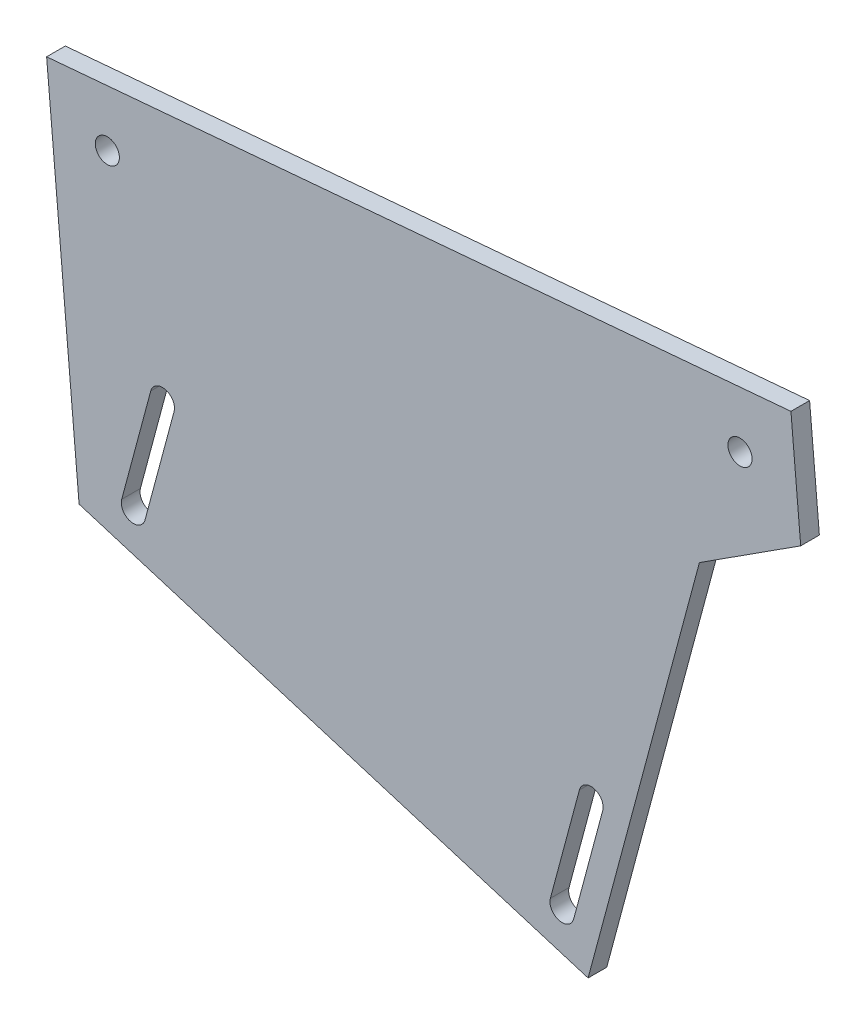
SolidWorks part; units mm, degrees
material "7075-T6, Plate (SS)"
ref_plane "Front Plane" through (0, 0, 0) normal (0, 0, 1) x (1, 0, 0)
ref_plane "Top Plane" through (0, 0, 0) normal (0, 1, 0) x (1, 0, 0)
ref_plane "Right Plane" through (0, 0, 0) normal (1, 0, 0) x (0, 0, -1)
sketch "Sketch1" plane through (0, 0, 0) normal (0, 0, 1) x (1, 0, 0)
  line L0 (-147.2071, -39.444) -> (0, 0) construction
  line L1 (0, 0) -> (-152.4, 0) construction
  line L2 (-425.45, 19.05) -> (-152.3665, -57.782)
  line L3 (-425.45, 57.15) -> (19.05, 57.15)
  line L4 (-425.45, 57.15) -> (-425.45, 19.05)
  line L6 (19.05, 57.15) -> (19.05, 0)
  line L7 (4.9305, -18.4009) -> (-142.2766, -57.8449)
  line L9 (-410.6516, 28.575) -> (19.05, 28.575) construction
  line L10 (-410.6516, 28.575) -> (-410.6516, -47.625) construction
  line L11 (-410.6516, -47.625) -> (19.05, -47.625) construction
  line L12 (19.05, 28.575) -> (19.05, -47.625) construction
  circle A0 centre (0, 0) radius 4.1021
  arc A1 (-152.4, 0) -> (-147.2071, -39.444) centre (0, 0) ccw construction
  arc A2 (-156.5021, 0) -> (-151.1694, -40.5057) centre (0, 0) ccw
  arc A3 (-148.2979, 0) -> (-143.2448, -38.3823) centre (0, 0) ccw
  arc A4 (-156.5021, 0) -> (-148.2979, 0) centre (-152.4, 0) cw
  arc A5 (-151.1694, -40.5057) -> (-143.2448, -38.3823) centre (-147.2071, -39.444) ccw
  circle A6 centre (-406.4, 38.1) radius 4.1021
  circle A7 centre (-101.6, 38.1) radius 4.1021
  arc A8 (-152.3665, -57.782) -> (-142.2766, -57.8449) centre (-147.2071, -39.444) ccw
  arc A9 (4.9305, -18.4009) -> (19.05, 0) centre (0, 0) ccw
  point P20 (19.05, -14.6176)
  dimension "D1" = 8.2042
  dimension "D2" = 152.4
  dimension "D6" = 304.8
  dimension "D3" = 15
  dimension "D7" = 38.1
  dimension "D8" = 101.6
  dimension "D9" = 19.05
  dimension "D10" = 19.05
  dimension "D11" = 19.05
  dimension "D13" = 19.05
  dimension "D16" = 76.2
  dimension "D4" = 4.1021
  dimension "D5" = 4.1021
extrude "Boss-Extrude1" [suppressed] add sketch "Sketch1" along normal blind 6.35
sketch "Sketch2" plane through (0, 0, 0) normal (0, 0, 1) x (1, 0, 0)
  line L0 (184.4812, 121.5931) -> (399.5596, 140.4101) construction
  line L1 (0, 0) -> (530.3185, 0) construction
  line L2 (0, 0) -> (0, 76.2) construction
  line L3 (0, 76.2) -> (530.3185, 76.2) construction
  line L4 (530.3185, 0) -> (530.3185, 76.2) construction
  line L5 (0, 0) -> (530.3185, 0) construction
  line L6 (0, 0) -> (0, 19.05) construction
  line L7 (0, 19.05) -> (530.3185, 19.05) construction
  line L8 (530.3185, 0) -> (530.3185, 19.05) construction
  line L9 (0, 76.2) -> (530.3185, 76.2) construction
  line L10 (0, 76.2) -> (0, 57.15) construction
  line L11 (0, 57.15) -> (530.3185, 57.15) construction
  line L12 (530.3185, 76.2) -> (530.3185, 57.15) construction
  line L13 (163.8434, 138.9103) -> (416.8768, 161.0479)
  line L14 (203.2, 57.15) -> (193.339, 20.3482) construction
  line L15 (207.1623, 56.0883) -> (197.3013, 19.2865)
  line L16 (199.2377, 58.2117) -> (189.3767, 21.4099)
  line L17 (348.9219, 12.5307) -> (339.0609, -24.2711) construction
  line L18 (352.8842, 11.469) -> (343.0232, -25.3328)
  line L19 (344.9596, 13.5924) -> (335.0986, -23.2094)
  line L20 (163.8434, 138.9103) -> (181.0028, -57.2221)
  line L21 (181.0028, -57.2221) -> (434.0362, -35.0846)
  line L22 (416.8768, 161.0479) -> (434.0362, -35.0846)
  line L24 (167.164, 100.9553) -> (420.1975, 123.0929)
  line L25 (174.8839, 12.7171) -> (353.8971, -42.0958)
  line L26 (193.339, 20.3482) -> (339.0609, -24.2711) construction
  line L27 (203.2, 57.15) -> (339.0609, -24.2711) construction
  line L28 (347.2776, -42.675) -> (385.7638, 100.9575)
  line L29 (385.7638, 100.9575) -> (420.1975, 123.0929)
  circle A0 centre (184.4812, 121.5931) radius 4.1021
  circle A1 centre (399.5596, 140.4101) radius 4.1021
  arc A2 (207.1623, 56.0883) -> (199.2377, 58.2117) centre (203.2, 57.15) ccw
  arc A3 (189.3767, 21.4099) -> (197.3013, 19.2865) centre (193.339, 20.3482) ccw
  arc A4 (352.8842, 11.469) -> (344.9596, 13.5924) centre (348.9219, 12.5307) ccw
  arc A5 (335.0986, -23.2094) -> (343.0232, -25.3328) centre (339.0609, -24.2711) ccw
  point P19 (198.2695, 38.7491)
  point P26 (343.9914, -5.8702)
  point P42 (384.0108, 94.4151)
  point P43 (193.339, 20.3482)
  dimension "D3" = 8.2042
  dimension "D4" = 19.05
  dimension "D1" = 76.2
  dimension "D2" = 19.05
  dimension "D5" = 8.2042
  dimension "D6" = 38.1
  dimension "D7" = 8.2042
  dimension "D8" = 38.1
  dimension "D9" = 19.05
  dimension "D10" = 19.05
  dimension "D11" = 254
  dimension "D12" = 76.2
  dimension "D13" = 19.05
  dimension "D14" = 20
  dimension "D15" = 19.05
  dimension "D16" = 19.05
  dimension "D17" = 152.4
  dimension "D18" = 20
  dimension "D19" = 203.2
  dimension "D20" = 38.1
  dimension "D21" = 5
  dimension "D22" = 12.7
  dimension "D23" = 12.7
  dimension "D24" = 19.05
extrude "Boss-Extrude2" add sketch "Sketch2" along normal blind 6.35 separate body contours L20 L25 L21 L22 L24 A5 L19 A4 L18 A3 L16 A2 L15 | L20 L24 L22 L13 A1 A0
